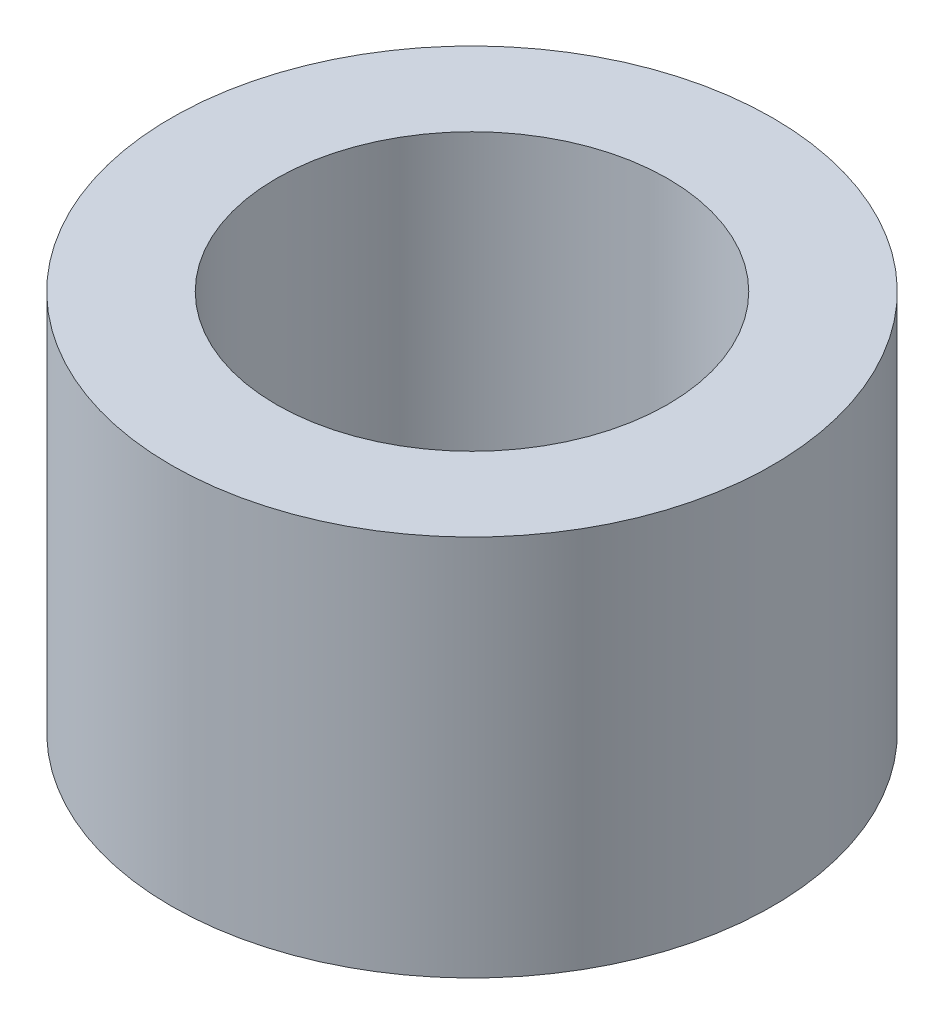
SolidWorks part; units mm, degrees
ref_plane "Front Plane" through (0, 0, 0) normal (0, 0, 1) x (1, 0, 0)
ref_plane "Top Plane" through (0, 0, 0) normal (0, 1, 0) x (1, 0, 0)
ref_plane "Right Plane" through (0, 0, 0) normal (1, 0, 0) x (0, 0, -1)
sketch "Sketch1" plane through (0, 0, 0) normal (0, 1, 0) x (1, 0, 0)
  circle A0 centre (0, 0) radius 3.15
  circle A1 centre (0, 0) radius 2.05
  dimension "D1" = 6.3
  dimension "D2" = 4.1
extrude "Boss-Extrude1" add sketch "Sketch1" along normal blind 4 contours A0 A1
